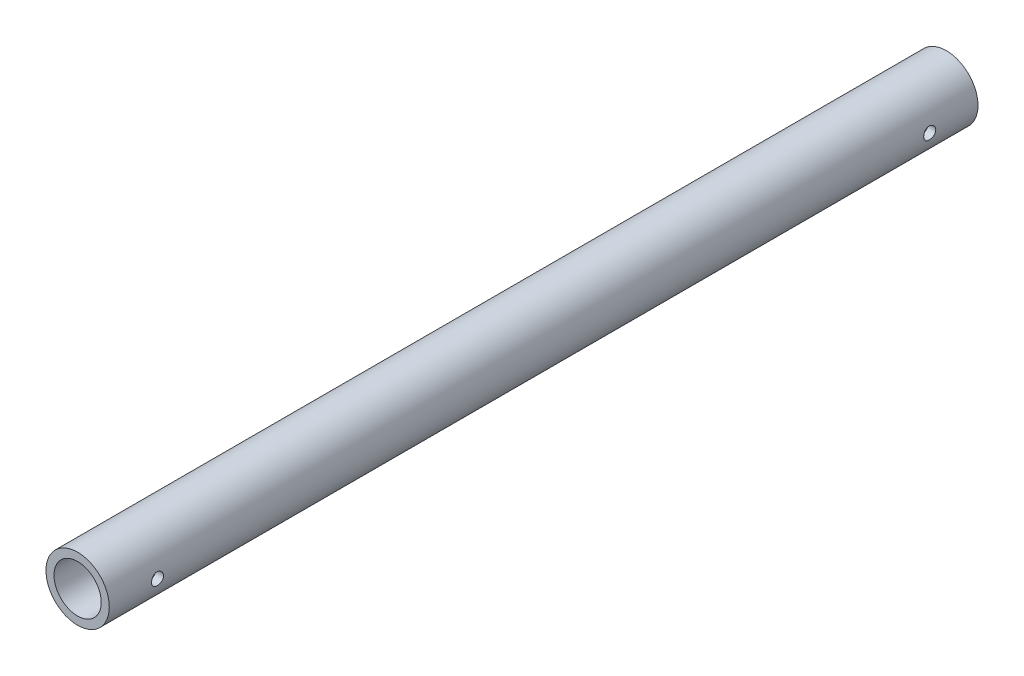
SolidWorks part; units mm, degrees
material "6061 Alloy"
ref_plane "Front Plane" through (0, 0, 0) normal (0, 0, 1) x (1, 0, 0)
ref_plane "Top Plane" through (0, 0, 0) normal (0, 1, 0) x (1, 0, 0)
ref_plane "Right Plane" through (0, 0, 0) normal (1, 0, 0) x (0, 0, -1)
sketch "Sketch1" plane through (0, 0, 0) normal (0, 0, 1) x (1, 0, 0)
  circle A0 centre (0, 0) radius 25
  circle A1 centre (0, 0) radius 18.65
  dimension "D1" = 6.35
  dimension "D2" = 50
extrude "Boss-Extrude1" add sketch "Sketch1" along normal blind 685.8
sketch "Sketch2" plane through (0, 0, 0) normal (1, 0, 0) x (0, 0, -1)
  line L0 (-685.8, 25) -> (-685.8, -25) construction
  line L1 (0, -25) -> (0, 25) construction
  circle A0 centre (-647.7, 0) radius 4.7625
  circle A1 centre (-38.1, 0) radius 4.7625
  point P4 (-685.8, 0)
  dimension "D1" = 9.525
  dimension "D2" = 38.1
  dimension "D3" = 38.1
extrude "Cut-Extrude1" cut sketch "Sketch2" against normal through all and the other way through all
